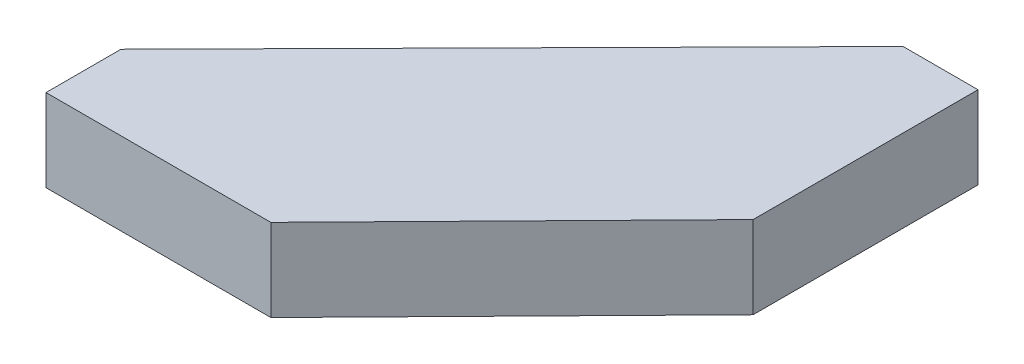
SolidWorks part; units mm, degrees
ref_plane "Front Plane" through (0, 0, 0) normal (0, 0, 1) x (1, 0, 0)
ref_plane "Top Plane" through (0, 0, 0) normal (0, 1, 0) x (1, 0, 0)
ref_plane "Right Plane" through (0, 0, 0) normal (1, 0, 0) x (0, 0, -1)
sketch "Sketch1" plane through (0, 0, 0) normal (0, 1, 0) x (1, 0, 0)
  line L0 (-15.4006, -14.3032) -> (-3.4006, -14.3032)
  line L1 (-3.4006, -14.3032) -> (9.3394, -1.3032)
  line L2 (9.3394, -1.3032) -> (9.3394, 10.6968)
  line L3 (9.3394, 10.6968) -> (5.3394, 10.6968)
  line L4 (5.3394, 10.6968) -> (-15.4006, -10.3032)
  line L5 (-15.4006, -10.3032) -> (-15.4006, -14.3032)
  dimension "D1" = 4
  dimension "D2" = 12
  dimension "D3" = 25
  dimension "D4" = 4
  dimension "D5" = 12
  dimension "D6" = 12.74
extrude "Boss-Extrude2" add sketch "Sketch1" along normal blind 4.4
sketch "Sketch11" plane through (0, 0, 0) normal (1, 0, 0) x (0, 0, -1)
  line L1 (-11.2762, 16.0114) -> (-1.0746, 16.0114)
  line L2 (-11.2762, 16.0114) -> (-11.2762, 6.8651)
  line L3 (-11.2762, 6.8651) -> (-1.0746, 6.8651)
  line L4 (-1.0746, 16.0114) -> (-1.0746, 6.8651)
